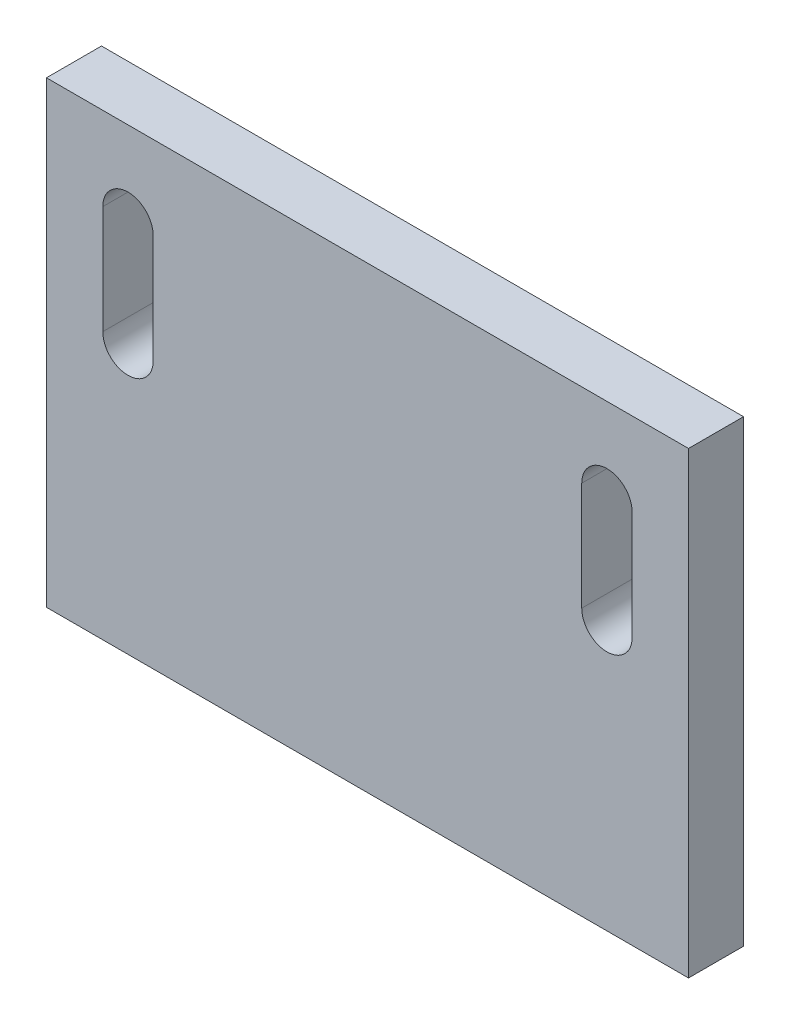
SolidWorks part; units mm, degrees
ref_plane "Front Plane" through (0, 0, 0) normal (0, 0, 1) x (1, 0, 0)
ref_plane "Top Plane" through (0, 0, 0) normal (0, 1, 0) x (1, 0, 0)
ref_plane "Right Plane" through (0, 0, 0) normal (1, 0, 0) x (0, 0, -1)
sketch "Sketch1" plane through (0, 0, 0) normal (0, 0, 1) x (1, 0, 0)
  line L1 (-35, -25) -> (35, -25)
  line L2 (-35, -25) -> (-35, 25)
  line L3 (-35, 25) -> (35, 25)
  line L4 (35, -25) -> (35, 25)
  line L5 (-35, -25) -> (35, 25) construction
  line L6 (-35, 25) -> (35, -25) construction
  point P0 (0, 0)
  dimension "D1" = 70
  dimension "D2" = 50
extrude "Boss-Extrude1" add sketch "Sketch1" along normal blind 6
sketch "Sketch2" plane through (0, 0, 0) normal (0, 0, 1) x (1, 0, 0)
  line L0 (0, -55) -> (0, 55) construction
  line L1 (-26.11, 4.0972) -> (-26.11, 15.9028) construction
  line L2 (35, 25) -> (-35, 25) construction
  line L3 (26.11, 4.0972) -> (26.11, 15.9028) construction
  line L4 (23.36, 4.0972) -> (23.36, 15.9028)
  line L5 (28.86, 4.0972) -> (28.86, 15.9028)
  line L6 (-23.36, 4.0972) -> (-23.36, 15.9028)
  line L7 (-28.86, 4.0972) -> (-28.86, 15.9028)
  circle A0 centre (26.11, 10) radius 2.75 construction
  arc A2 (23.36, 4.0972) -> (28.86, 4.0972) centre (26.11, 4.0972) ccw
  arc A3 (28.86, 15.9028) -> (23.36, 15.9028) centre (26.11, 15.9028) ccw
  arc A4 (-23.36, 4.0972) -> (-28.86, 4.0972) centre (-26.11, 4.0972) cw
  arc A5 (-28.86, 15.9028) -> (-23.36, 15.9028) centre (-26.11, 15.9028) cw
  circle A6 centre (-26.11, 10) radius 2.75 construction
  point P6 (26.11, 10)
  point P18 (-26.11, 10)
  dimension "D1" = 5.5
  dimension "D2" = 26.11
  dimension "D3" = 15
  dimension "D4" = 11.8055
extrude "Cut-Extrude1" cut sketch "Sketch2" along normal through all
